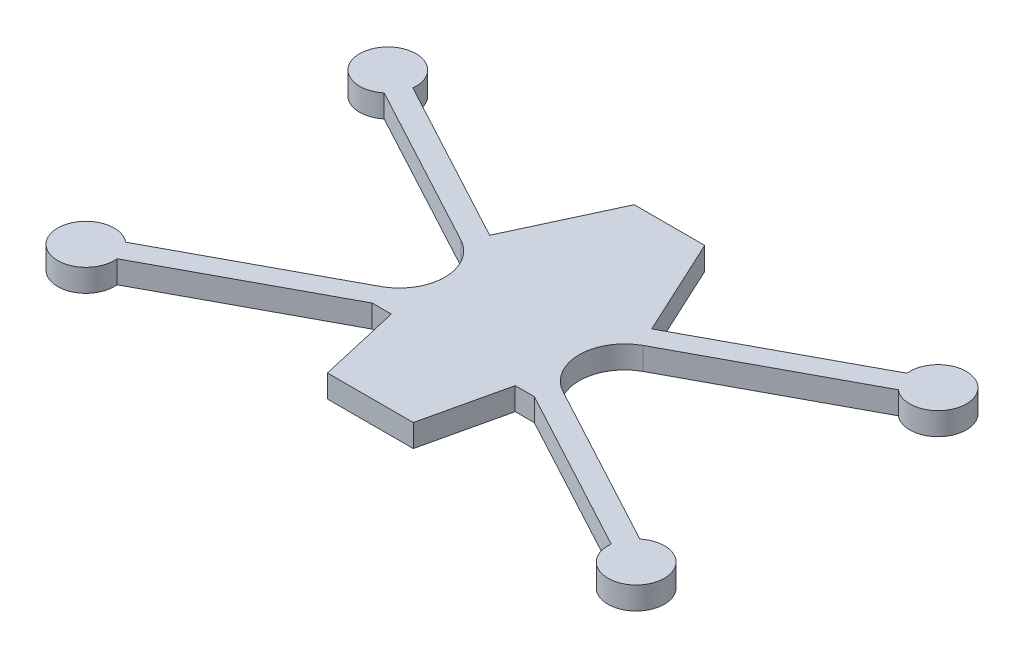
SolidWorks part; units mm, degrees
ref_plane "Front Plane" through (0, 0, 0) normal (0, 0, 1) x (1, 0, 0)
ref_plane "Top Plane" through (0, 0, 0) normal (0, 1, 0) x (1, 0, 0)
ref_plane "Right Plane" through (0, 0, 0) normal (1, 0, 0) x (0, 0, -1)
sketch "Sketch1" plane through (0, 0, 0) normal (0, 1, 0) x (1, 0, 0)
  line L0 (0, 301.9971) -> (0, -329.1707) construction
  line L1 (332.2586, 0) -> (-415.0145, 0) construction
  line L2 (-77.47, 44.45) -> (-247.65, 135.89) construction
  line L3 (-77.47, -44.45) -> (-247.65, -135.89) construction
  line L4 (77.47, -44.45) -> (225.2753, -123.8678) construction
  line L5 (247.65, 135.89) -> (77.47, 44.45) construction
  line L6 (-72.9617, 52.8405) -> (-222.3998, 133.1356)
  line L7 (-81.9783, 36.0595) -> (-231.4164, 116.3546)
  line L9 (252.1583, 127.4995) -> (81.9783, 36.0595) construction
  line L10 (-81.9783, -36.0595) -> (-231.4164, -116.3546)
  line L11 (-72.9617, -52.8405) -> (-222.3998, -133.1356)
  line L12 (243.1417, 144.2805) -> (72.9617, 52.8405) construction
  line L13 (-81.9783, 36.0595) -> (-252.1583, 127.4995) construction
  line L14 (72.9617, -52.8405) -> (222.3998, -133.1356)
  line L15 (81.9783, -36.0595) -> (231.4164, -116.3546)
  line L16 (81.9783, -36.0595) -> (252.1583, -127.4995) construction
  line L17 (-72.9617, -52.8405) -> (-243.1417, -144.2805) construction
  line L18 (222.3998, 133.1356) -> (72.9617, 52.8405)
  line L19 (231.4164, 116.3546) -> (81.9783, 36.0595)
  line L20 (77.47, -44.45) -> (247.65, -135.89) construction
  line L21 (72.9617, -52.8405) -> (243.1417, -144.2805) construction
  line L22 (-72.9617, 52.8405) -> (-31.75, 141.7405)
  line L23 (-31.75, 141.7405) -> (31.75, 141.7405)
  line L24 (31.75, 141.7405) -> (72.9617, 52.8405)
  line L25 (-72.9617, -52.8405) -> (-55.7652, -52.8405)
  line L26 (-55.7652, -52.8405) -> (-38.6253, -127.4995)
  line L27 (-38.6253, -127.4995) -> (0, -127.4995)
  line L28 (72.9617, -52.8405) -> (55.7652, -52.8405)
  line L29 (55.7652, -52.8405) -> (38.6253, -127.4995)
  line L30 (38.6253, -127.4995) -> (0, -127.4995)
  line L31 (-81.9783, -36.0595) -> (-252.1583, -127.4995) construction
  line L32 (-72.9617, 52.8405) -> (-243.1417, 144.2805) construction
  arc A0 (231.4164, 116.3546) -> (222.3998, 133.1356) centre (247.65, 135.89) ccw
  arc A1 (222.3998, -133.1356) -> (231.4164, -116.3546) centre (247.65, -135.89) ccw
  arc A2 (-231.4164, -116.3546) -> (-222.3998, -133.1356) centre (-247.65, -135.89) ccw
  arc A3 (-222.3998, 133.1356) -> (-231.4164, 116.3546) centre (-247.65, 135.89) ccw
  arc A4 (-81.9783, 36.0595) -> (-81.9783, -36.0595) centre (-101.3536, 0) cw
  arc A5 (81.9783, 36.0595) -> (81.9783, -36.0595) centre (101.3536, 0) ccw
  point P0 (247.65, 135.89)
  point P1 (-247.65, 135.89)
  point P2 (-247.65, -135.89)
  point P3 (247.65, -135.89)
  point P4 (77.47, -44.45)
  point P5 (77.47, 44.45)
  point P6 (-77.47, 44.45)
  point P7 (-77.47, -44.45)
  dimension "D9" = 9.525
  dimension "D1" = 495.3
  dimension "D2" = 271.78
  dimension "D3" = 154.94
  dimension "D4" = 88.9
  dimension "D5" = 247.65
  dimension "D6" = 135.89
  dimension "D7" = 44.45
  dimension "D8" = 77.47
  dimension "D17" = 63.5
  dimension "D18" = 88.9
  dimension "D10" = 9.525
  dimension "D11" = 9.525
  dimension "D12" = 9.525
  dimension "D13" = 9.525
  dimension "D14" = 9.525
  dimension "D15" = 9.525
  dimension "D16" = 9.525
extrude "Boss-Extrude1" add sketch "Sketch1" along normal blind 20.32
